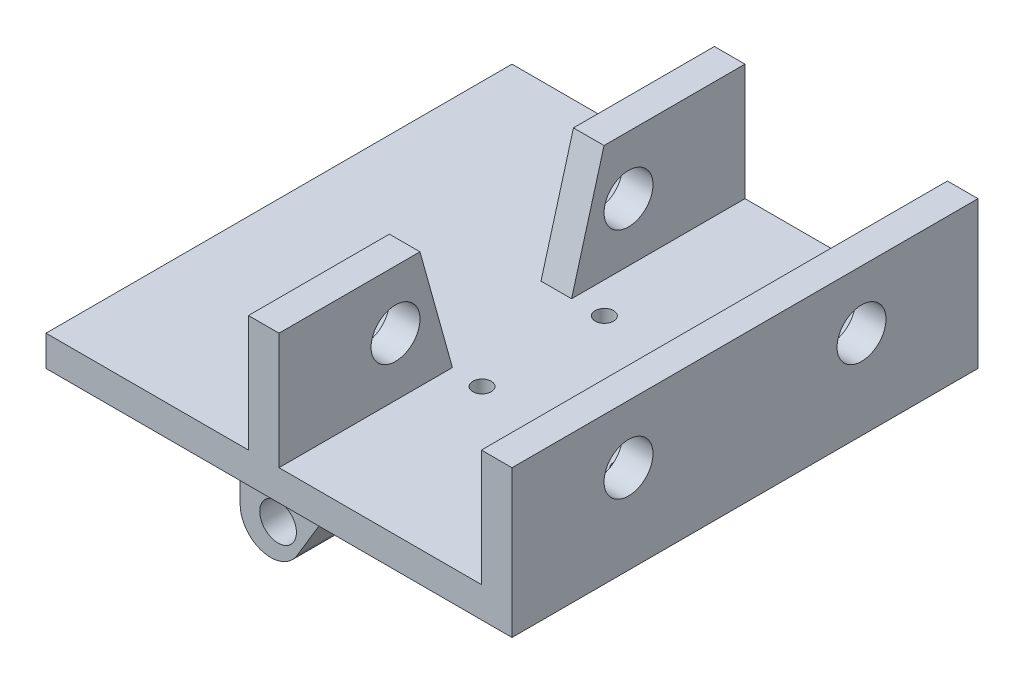
SolidWorks part; units mm, degrees
ref_plane "Front Plane" through (0, 0, 0) normal (0, 0, 1) x (1, 0, 0)
ref_plane "Top Plane" through (0, 0, 0) normal (0, 1, 0) x (1, 0, 0)
ref_plane "Right Plane" through (0, 0, 0) normal (1, 0, 0) x (0, 0, -1)
sketch "Sketch2" plane through (0, 0, 0) normal (0, 1, 0) x (1, 0, 0)
  line L0 (-51.309, 0) -> (76.3758, 0) construction
  line L1 (-38.1, 38.1) -> (38.1, 38.1)
  line L2 (-38.1, 38.1) -> (-38.1, -38.1)
  line L3 (-38.1, -38.1) -> (38.1, -38.1)
  line L4 (38.1, 38.1) -> (38.1, -38.1)
  line L5 (-38.1, 38.1) -> (38.1, -38.1) construction
  line L6 (-38.1, -38.1) -> (38.1, 38.1) construction
  circle A5 centre (28.1, 10) radius 1.5
  circle A6 centre (5.1, 10) radius 1.5
  circle A7 centre (28.1, -10) radius 1.5
  circle A8 centre (5.1, -10) radius 1.5
  point P0 (0, 0)
  dimension "D3" = 3
  dimension "D5" = 3
  dimension "D7" = 10
  dimension "D1" = 76.2
  dimension "D2" = 76.2
  dimension "D4" = 10
  dimension "D6" = 23
extrude "Boss-Extrude1" add sketch "Sketch2" along normal blind 5
sketch "Sketch3" plane through (38.1, 0, 0) normal (1, 0, 0) x (0, 0, -1)
  line L0 (-38.1, 5) -> (38.1, 5) construction
  line L1 (-38.1, 0) -> (38.1, 0)
  line L2 (-38.1, 0) -> (-38.1, 24.05)
  line L3 (-38.1, 24.05) -> (38.1, 24.05)
  line L4 (38.1, 0) -> (38.1, 24.05)
  circle A0 centre (-19.05, 14.525) radius 4
  circle A1 centre (19.05, 14.525) radius 4
  dimension "D2" = 8
  dimension "D3" = 8
  dimension "D1" = 19.05
  dimension "D4" = 19.05
  dimension "D5" = 19.05
  dimension "D6" = 9.525
  dimension "D7" = 9.525
extrude "Boss-Extrude2" add sketch "Sketch3" against normal blind 5
pattern_linear "LPattern1" count 2 spacing 38.1 along (-1, 0, 0) of "Boss-Extrude2"
sketch "Sketch4" plane through (0, 0, -38.1) normal (0, 0, -1) x (-1, 0, 0)
  line L4 (6.1, 0) -> (38.1, 0)
  line L5 (-38.1, 0) -> (38.1, 0) construction
  line L7 (38.1, 0) -> (38.1, -35.1483)
  line L8 (28.8166, -37.7274) -> (6.1, 0)
  line L9 (-16.6, 24.2409) -> (-16.6, -27.2898) construction
  line L10 (-38.1, 24.05) -> (-38.1, 0) construction
  line L11 (47.8555, -16.5) -> (-55.5186, -16.5) construction
  circle A1 centre (31.9, -34.5) radius 3
  arc A2 (38.1, -35.1483) -> (28.8166, -37.7274) centre (33.1, -35.1483) cw
  point P15 (38.1, -51.7688)
  point P17 (38.1, -53.1453)
  point P18 (25.3279, -39.9828)
  dimension "D2" = 16.5
  dimension "D5" = 6
  dimension "D4" = 5
  dimension "D1" = 21.5
  dimension "D3" = 32
  dimension "D6" = 18
  dimension "D7" = 48.5
extrude "Boss-Extrude5" add sketch "Sketch4" against normal mid plane 12.7 from offset 38.1 offset against normal yes
sketch "Sketch5" plane through (0, 0, 0) normal (1, 0, 0) x (0, 0, -1)
  line L0 (38.1, 24.05) -> (-38.1, 24.05) construction
  line L5 (9.7433, 5) -> (-9.7433, 5)
  line L7 (0, 24.05) -> (-9.7433, 5) construction
  line L8 (9.7433, 5) -> (0, 24.05) construction
  line L9 (38.1, 5) -> (-38.1, 5) construction
  line L10 (-15.05, 24.05) -> (-9.7433, 5)
  line L11 (15.05, 24.05) -> (9.7433, 5)
  line L12 (-15.05, 24.05) -> (-9.7433, 24.05)
  line L13 (15.05, 24.05) -> (9.7433, 24.05)
  line L14 (-9.7433, 24.05) -> (9.7433, 24.05)
  point P0 (0, 24.05)
extrude "Cut-Extrude1" cut sketch "Sketch5" against normal blind 10
